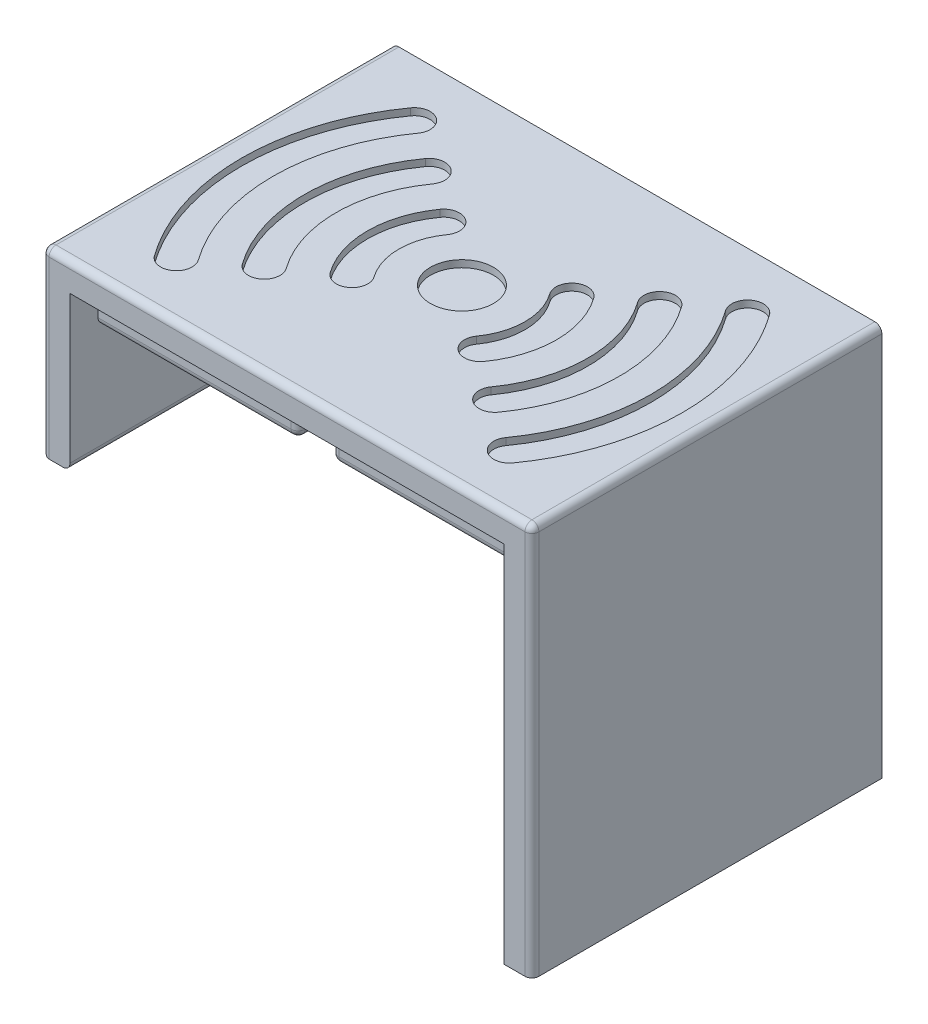
SolidWorks part; units mm, degrees
ref_plane "Front Plane" through (0, 0, 0) normal (0, 0, 1) x (1, 0, 0)
ref_plane "Top Plane" through (0, 0, 0) normal (0, 1, 0) x (1, 0, 0)
ref_plane "Right Plane" through (0, 0, 0) normal (1, 0, 0) x (0, 0, -1)
sketch "Sketch1" plane through (0, 0, 0) normal (0, 1, 0) x (1, 0, 0)
  line L0 (-17.5, 12.5) -> (17.5, -12.5) construction
  line L1 (-17.5, 12.5) -> (17.5, 12.5)
  line L2 (-17.5, 12.5) -> (-17.5, -12.5)
  line L3 (-17.5, -12.5) -> (17.5, -12.5)
  line L4 (17.5, 12.5) -> (17.5, -12.5)
  dimension "D1" = 25
  dimension "D2" = 35
extrude "Boss-Extrude1" add sketch "Sketch1" along normal blind 2
sketch "Sketch3" plane through (0, 0, 0) normal (0, -1, 0) x (-1, 0, 0)
  line L0 (-17.5, 12.5) -> (17.5, 12.5) construction
  line L1 (17.5, -12.5) -> (15.5, -12.5)
  line L2 (17.5, -12.5) -> (17.5, 12.5)
  line L3 (17.5, 12.5) -> (15.5, 12.5)
  line L4 (15.5, -12.5) -> (15.5, 12.5)
  dimension "D1" = 2
extrude "Boss-Extrude3" add sketch "Sketch3" along normal blind 11
sketch "Sketch4" plane through (0, 0, 0) normal (0, -1, 0) x (1, 0, 0)
  line L0 (17.5, -12.5) -> (-15.5, -12.5) construction
  line L1 (17.5, 12.5) -> (15.5, 12.5)
  line L2 (17.5, 12.5) -> (17.5, -12.5)
  line L3 (17.5, -12.5) -> (15.5, -12.5)
  line L4 (15.5, 12.5) -> (15.5, -12.5)
  dimension "D1" = 2
extrude "Boss-Extrude4" add sketch "Sketch4" along normal blind 26
sketch "Sketch5" plane through (0, 0, 0) normal (0, -1, 0) x (1, 0, 0)
  line L0 (-15.5, -12.5) -> (-15.5, 12.5) construction
  line L1 (-15.5, 10.5) -> (15.5, 10.5)
  line L2 (-15.5, 10.5) -> (-15.5, 8.5)
  line L3 (-15.5, 8.5) -> (15.5, 8.5)
  line L4 (15.5, 10.5) -> (15.5, 8.5)
  line L5 (15.5, 12.5) -> (15.5, -12.5) construction
  line L6 (-1.2, -10.5) -> (1.2, 10.5) construction
  line L7 (15.5, -10.5) -> (-15.5, -10.5)
  line L8 (15.5, -10.5) -> (15.5, -8.5)
  line L9 (15.5, -8.5) -> (-15.5, -8.5)
  line L10 (-15.5, -10.5) -> (-15.5, -8.5)
  line L11 (-1.2, 10.5) -> (1.2, 10.5)
  line L12 (-1.2, 10.5) -> (-1.2, -10.5)
  line L13 (-1.2, -10.5) -> (1.2, -10.5)
  line L14 (1.2, 10.5) -> (1.2, -10.5)
  line L15 (-15.5, 12.5) -> (15.5, 12.5) construction
  line M14 (15.5, -12.5) -> (15.5, 12.5)
  line M16 (-15.5, 12.5) -> (-15.5, -12.5)
  dimension "D1" = 2
  dimension "D2" = 2
  dimension "D3" = 2.4
extrude "Boss-Extrude5" add sketch "Sketch5" along normal blind 3 contours L1 L14 L3 M14 | L12 L1 L3 M16 | L12 L9 L7 M16 | L9 L14 L7 M14
sketch "Sketch6" plane through (0, 2, 0) normal (0, 1, 0) x (1, 0, 0)
  line L0 (-2.25, 0) -> (-4.5, 0) construction
  line L1 (-4.5, 0) -> (-6.75, 0) construction
  line L2 (-6.75, 0) -> (-9, 0) construction
  line L3 (-9, 0) -> (-11.25, 0) construction
  line L4 (-11.25, 0) -> (-13.5, 0) construction
  line L5 (-13.5, 0) -> (-15.75, 0) construction
  line L7 (-17.5, 12.5) -> (17.5, -12.5) construction
  line L8 (-17.5, -12.5) -> (17.5, 12.5) construction
  circle A0 centre (0, 0) radius 2.25
  circle A1 centre (0, 0) radius 11.25
  circle A2 centre (0, 0) radius 9
  circle A3 centre (0, 0) radius 6.75
  circle A4 centre (0, 0) radius 4.5
  circle A6 centre (0, 0) radius 13.5
  circle A7 centre (0, 0) radius 15.75
  circle A8 centre (-4.5773, 3.2695) radius 1.125
  circle A9 centre (-8.2391, 5.885) radius 1.125
  circle A10 centre (-11.9009, 8.5006) radius 1.125
  circle A11 centre (-4.5773, -3.2695) radius 1.125
  circle A12 centre (-8.2391, -5.885) radius 1.125
  circle A13 centre (-11.9009, -8.5006) radius 1.125
  circle A14 centre (4.5773, 3.2695) radius 1.125
  circle A15 centre (8.2391, 5.885) radius 1.125
  circle A16 centre (11.9009, 8.5006) radius 1.125
  circle A17 centre (11.9009, -8.5006) radius 1.125
  circle A18 centre (8.2391, -5.885) radius 1.125
  circle A19 centre (4.5773, -3.2695) radius 1.125
  dimension "D1" = 4.5
  dimension "D2" = 2.25
extrude "Cut-Extrude1" cut sketch "Sketch6" against normal blind 0.5 contours A0 | A19 A3 A14 A4 | A18 A1 A15 A2 | A17 A7 A16 A6 | A11 A4 A8 A3 | A12 A2 A9 A1 | A13 A6 A10 A7 | A10 | A9 | A8 | A11 | A12 | A13 | A18 | A19 | A14 | A15 | A16 | A17
fillet "Fillet1" radius 0.5 30 edges at (-17.5, 2, 0) (-17.5, -4.5, 12.5) (-17.5, -11, 0) (17.5, 2, 0) (17.5, -12, 12.5) (15.5, 0, 0) (-15.5, 0, 0) (8.35, -3, -8.5) (-8.35, -3, -8.5) (-8.35, -3, 8.5) (-8.35, -3, 10.5) (8.35, -3, 10.5) (-1.2, -1.5, 10.5) (-1.2, -1.5, 8.5) (1.2, -3, 9.5) (1.2, -1.5, 10.5) (1.2, -1.5, 8.5) (-1.2, -1.5, -10.5) (-1.2, -1.5, -8.5) (1.2, -1.5, -8.5) (1.2, -1.5, -10.5) (8.35, -3, -10.5) (-8.35, -3, -10.5) (0, 2, 12.5) (-15.5, -11, 0) (-1.2, -3, 9.5) (-1.2, -3, -9.5) (1.2, -3, -9.5) (15.5, -13, -12.5) (-15.5, -5.5, -12.5)
